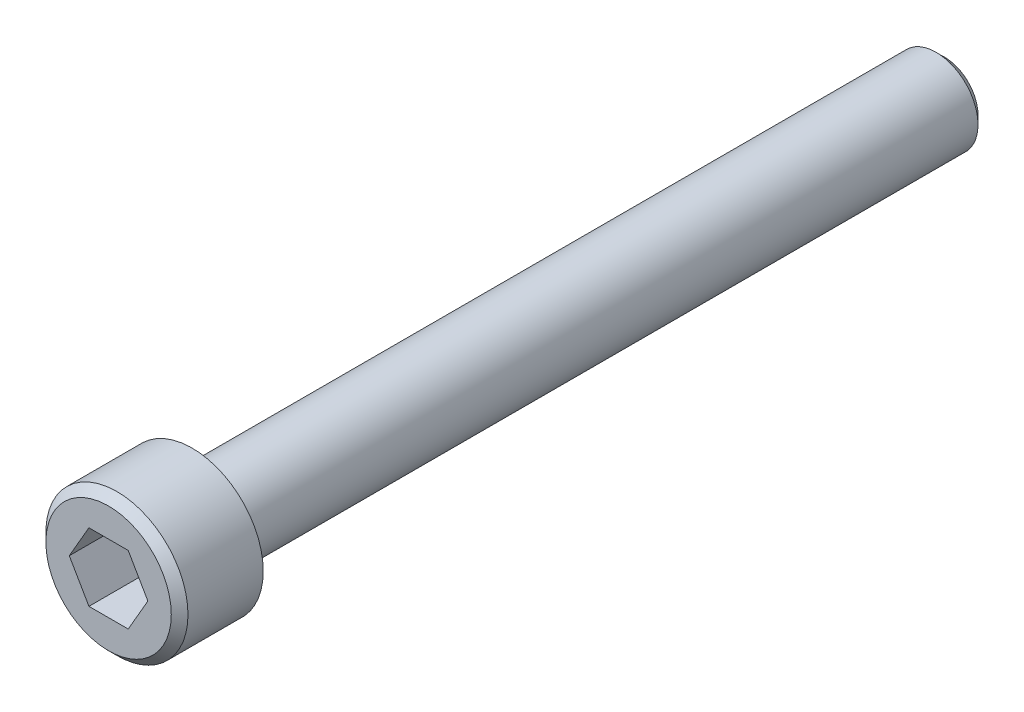
SolidWorks part; units mm, degrees
ref_plane "Alzado" through (0, 0, 0) normal (0, 0, 1) x (1, 0, 0)
ref_plane "Planta" through (0, 0, 0) normal (0, 1, 0) x (1, 0, 0)
ref_plane "Vista lateral" through (0, 0, 0) normal (1, 0, 0) x (0, 0, -1)
sketch "Croquis1" plane through (0, 0, 0) normal (0, 0, 1) x (1, 0, 0)
  circle A0 centre (0, 0) radius 4.25
  dimension "D1" = 8.5
extrude "Saliente-Extruir1" add sketch "Croquis1" along normal blind 5
sketch "Croquis2" plane through (0, 0, 0) normal (0, 0, -1) x (-1, 0, 0)
  circle A0 centre (0, 0) radius 2.5
  dimension "D1" = 5
extrude "Saliente-Extruir2" add sketch "Croquis2" along normal blind 45
chamfer "Chaflán1" distance 0.5 angle 45 2 edges at (4.25, 0, 5) (-2.5, 0, -45)
sketch "Croquis3" plane through (0, 0, 5) normal (0, 0, 1) x (1, 0, 0)
  line L1 (2.35, 0) -> (1.175, 2.0352)
  line L2 (1.175, 2.0352) -> (-1.175, 2.0352)
  line L3 (-1.175, 2.0352) -> (-2.35, 0)
  line L4 (-2.35, 0) -> (-1.175, -2.0352)
  line L5 (-1.175, -2.0352) -> (1.175, -2.0352)
  line L6 (1.175, -2.0352) -> (2.35, 0)
  circle A0 centre (0, 0) radius 2.0352 construction
  dimension "D1" = 4.7
extrude "Cortar-Extruir1" cut sketch "Croquis3" against normal blind 3.5
